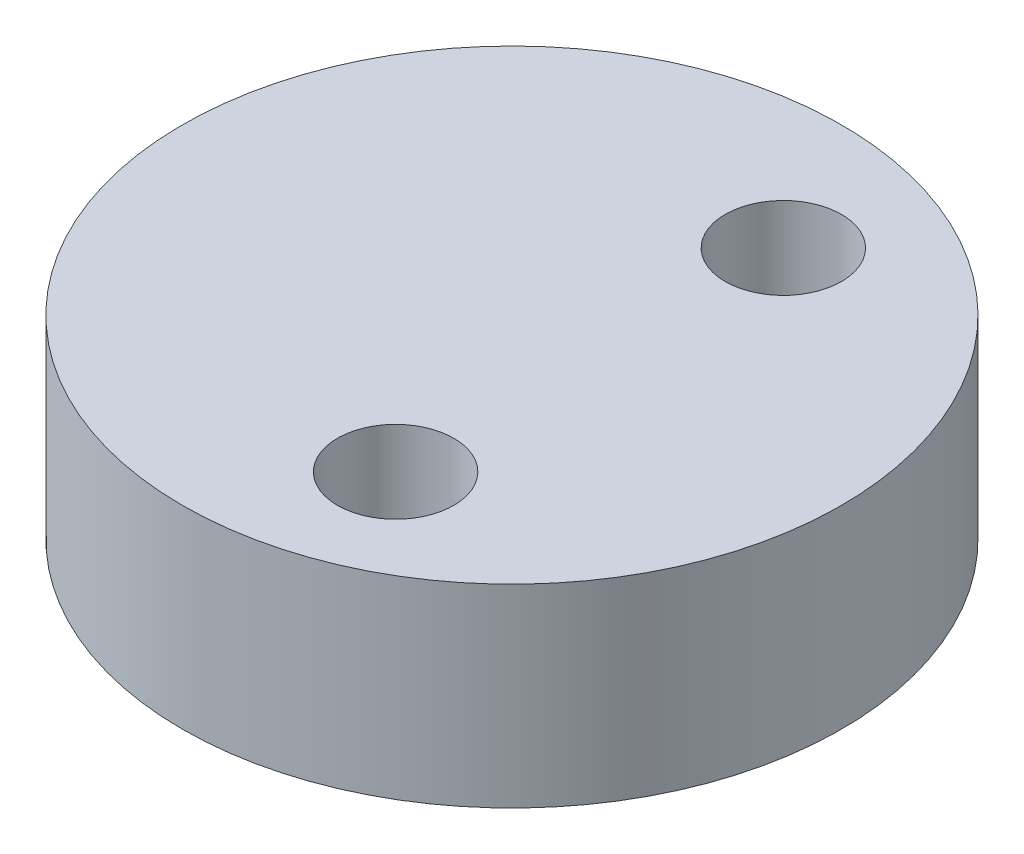
SolidWorks part; units mm, degrees
ref_plane "Front Plane" through (0, 0, 0) normal (0, 0, 1) x (1, 0, 0)
ref_plane "Top Plane" through (0, 0, 0) normal (0, 1, 0) x (1, 0, 0)
ref_plane "Right Plane" through (0, 0, 0) normal (1, 0, 0) x (0, 0, -1)
sketch "Sketch1" plane through (0, 0, 0) normal (0, 1, 0) x (1, 0, 0)
  line L0 (0, 0) -> (-2, 0) construction
  circle A0 centre (0, 0) radius 5 construction
  circle A1 centre (-2, 0) radius 8.5
  circle A3 centre (0, 5) radius 1.5
  circle A4 centre (0, -5) radius 1.5
  point P12 (0, 0)
  dimension "D1" = 10
  dimension "D3" = 17
  dimension "D5" = 3
  dimension "D2" = 2
  dimension "D6" = 2
extrude "Boss-Extrude1" add sketch "Sketch1" along normal blind 5
